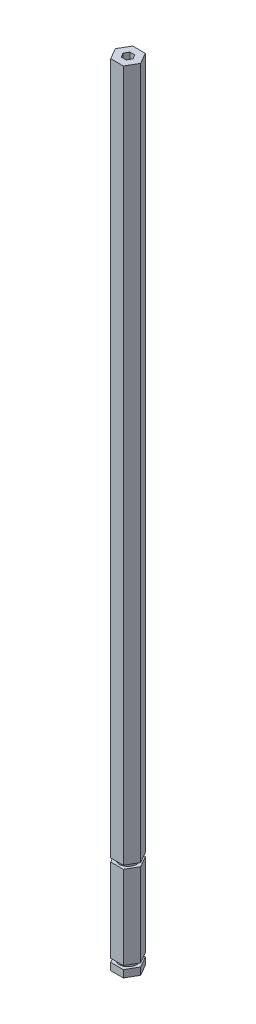
SolidWorks part; units mm, degrees
ref_plane "Front Plane" through (0, 0, 0) normal (0, 0, 1) x (1, 0, 0)
ref_plane "Top Plane" through (0, 0, 0) normal (0, 1, 0) x (1, 0, 0)
ref_plane "Right Plane" through (0, 0, 0) normal (1, 0, 0) x (0, 0, -1)
sketch "Sketch1" plane through (0, 0, 0) normal (0, 1, 0) x (1, 0, 0)
  line L9 (7.3323, 0) -> (3.6662, 6.35)
  line L10 (3.6662, 6.35) -> (-3.6662, 6.35)
  line L11 (-3.6662, 6.35) -> (-7.3323, 0)
  line L12 (-7.3323, 0) -> (-3.6662, -6.35)
  line L13 (-3.6662, -6.35) -> (3.6662, -6.35)
  line L14 (3.6662, -6.35) -> (7.3323, 0)
  line L15 (1.4434, 2.5) -> (-1.4434, 2.5)
  line L16 (-1.4434, 2.5) -> (-2.8868, 0)
  line L17 (-2.8868, 0) -> (-1.4434, -2.5)
  line L18 (-1.4434, -2.5) -> (1.4434, -2.5)
  line L19 (1.4434, -2.5) -> (2.8868, 0)
  line L20 (2.8868, 0) -> (1.4434, 2.5)
  circle A0 centre (0, 0) radius 6.35 construction
  circle A1 centre (0, 0) radius 2.5 construction
  dimension "D1" = 12.7
  dimension "D2" = 5
extrude "Boss-Extrude1" add sketch "Sketch1" along normal blind 457.2
sketch "Sketch3" plane through (0, 0, 0) normal (1, 0, 0) x (0, 0, -1)
  line L0 (0, 457.2) -> (0, 431.8613) construction
  line L2 (0, 457.2) -> (0, 0) construction
  line L7 (-5.0165, 56.515) -> (5.0165, 56.515) construction
  line L10 (5.0165, 56.515) -> (7.5565, 56.515)
  line L11 (5.0165, 56.515) -> (5.0165, 54.483)
  line L12 (5.0165, 54.483) -> (7.5565, 54.483)
  line L13 (7.5565, 56.515) -> (7.5565, 54.483)
  line L14 (0, 0) -> (6.35, 0) construction
  line L15 (5.0165, 54.483) -> (5.0165, 6.223) construction
  line L16 (5.0165, 30.353) -> (-13.2923, 30.353) construction
  line L17 (5.0165, 4.191) -> (7.5565, 4.191)
  line L18 (5.0165, 4.191) -> (5.0165, 6.223)
  line L19 (5.0165, 6.223) -> (7.5565, 6.223)
  line L20 (7.5565, 4.191) -> (7.5565, 6.223)
  point P7 (0, 56.515)
  dimension "D1" = 10.033
  dimension "D2" = 54.483
  dimension "D3" = 2.032
  dimension "D4" = 2.54
  dimension "D5" = 48.26
revolve "Cut-Revolve2" cut sketch "Sketch3" angle 360 about L0
